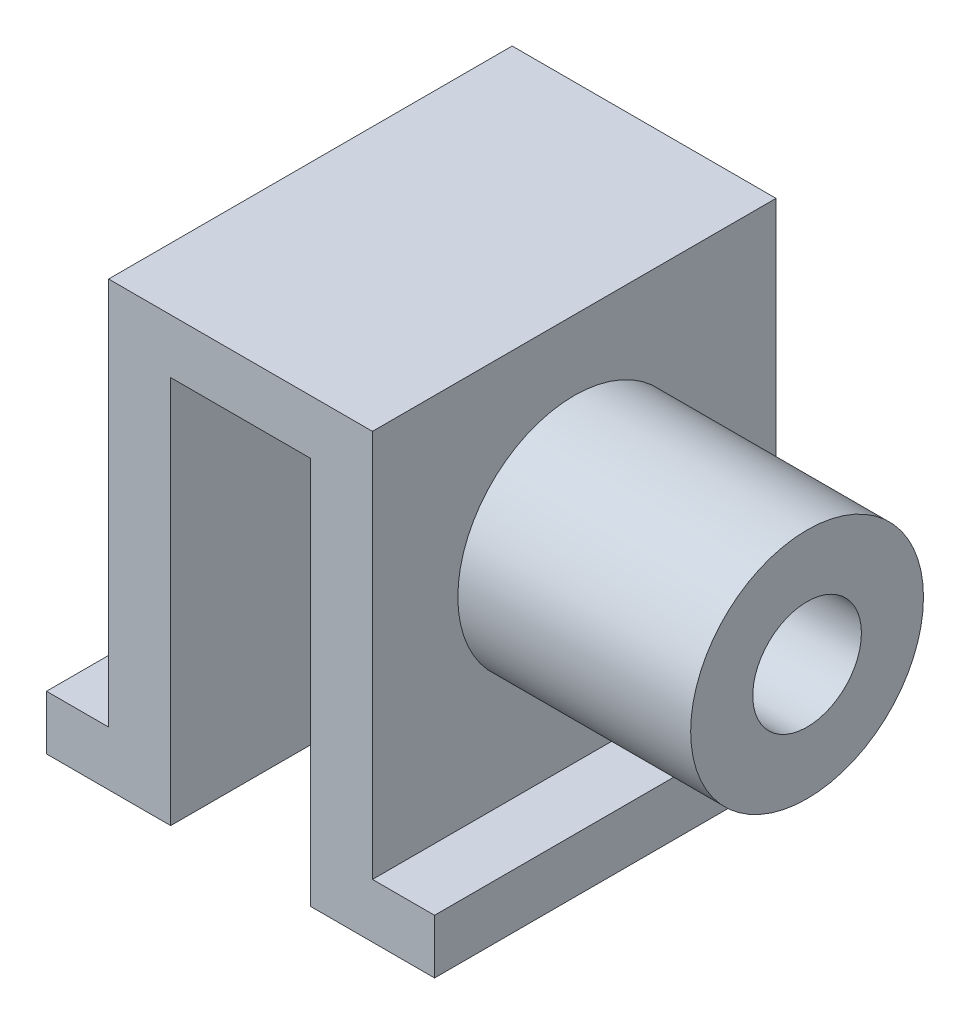
SolidWorks part; units mm, degrees
ref_plane "Front Plane" through (0, 0, 0) normal (0, 0, 1) x (1, 0, 0)
ref_plane "Top Plane" through (0, 0, 0) normal (0, 1, 0) x (1, 0, 0)
ref_plane "Right Plane" through (0, 0, 0) normal (1, 0, 0) x (0, 0, -1)
sketch "Sketch1" plane through (0, 0, 0) normal (0, 0, 1) x (1, 0, 0)
  line L1 (0, 0) -> (50, 0)
  line L2 (0, 0) -> (0, 57)
  line L3 (0, 57) -> (50, 57)
  line L4 (50, 0) -> (50, 57)
  dimension "D1" = 50
  dimension "D2" = 57
extrude "Boss-Extrude1" add sketch "Sketch1" against normal blind 52
sketch "Sketch2" plane through (0, 0, 0) normal (0, 0, 1) x (1, 0, 0)
  line L0 (16, 50) -> (34, 50)
  line L1 (34, 50) -> (34, 0)
  line L2 (0, 0) -> (50, 0) construction
  line L3 (34, 0) -> (16, 0)
  line L4 (16, 0) -> (16, 50)
  line L6 (50, 57) -> (0, 57) construction
  dimension "D1" = 7
  dimension "D2" = 16
  dimension "D3" = 16
extrude "Cut-Extrude1" cut sketch "Sketch2" against normal blind 52
sketch "Sketch3" plane through (0, 0, 0) normal (0, 0, 1) x (1, 0, 0)
  line L0 (50, 7) -> (42, 7)
  line L1 (50, 0) -> (50, 57) construction
  line L2 (42, 7) -> (42, 57)
  line L3 (50, 57) -> (0, 57) construction
  line L4 (42, 57) -> (50, 57)
  line L5 (50, 57) -> (50, 7)
  line L6 (0, 7) -> (8, 7)
  line L7 (0, 57) -> (0, 0) construction
  line L8 (8, 7) -> (8, 57)
  line L9 (8, 57) -> (0, 57)
  line L10 (0, 57) -> (0, 7)
  line L11 (16, 50) -> (16, 0) construction
  line L12 (34, 0) -> (34, 50) construction
  point P13 (0, 0)
  dimension "D1" = 7
  dimension "D2" = 8
  dimension "D3" = 8
extrude "Cut-Extrude2" cut sketch "Sketch3" against normal blind 52
sketch "Sketch4" plane through (42, 0, 0) normal (1, 0, 0) x (0, 0, -1)
  line L0 (52, 57) -> (0, 57) construction
  circle A0 centre (26, 33) radius 15
  circle A1 centre (26, 33) radius 7
  point P3 (0, 0)
  point P6 (26, 57)
  dimension "D1" = 14
  dimension "D2" = 30
  dimension "D3" = 24
extrude "Boss-Extrude2" add sketch "Sketch4" along normal blind 30
